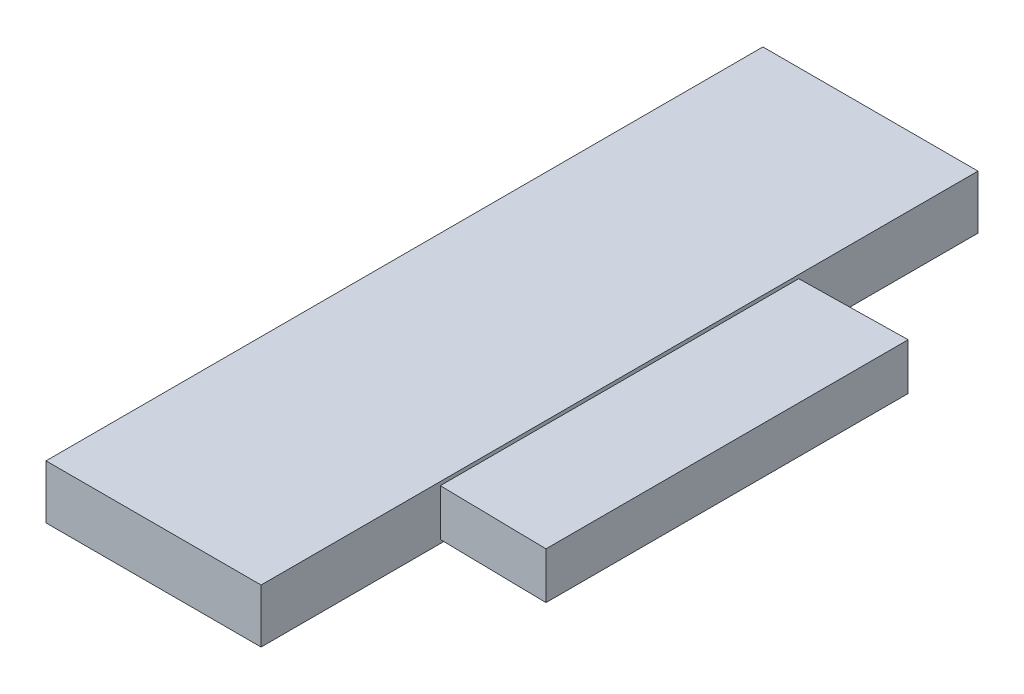
SolidWorks part; units mm, degrees
material "99.5% Aluminum Oxide (2)"
ref_plane "Front Plane" through (0, 0, 0) normal (0, 0, 1) x (1, 0, 0)
ref_plane "Top Plane" through (0, 0, 0) normal (0, 1, 0) x (1, 0, 0)
ref_plane "Right Plane" through (0, 0, 0) normal (1, 0, 0) x (0, 0, -1)
sketch "Sketch1" plane through (0, 0, 0) normal (0, 1, 0) x (1, 0, 0)
  line L1 (-30, 50) -> (0, 50)
  line L2 (-30, 50) -> (-30, -50)
  line L3 (-30, -50) -> (0, -50)
  line L7 (0, 50) -> (0, -50)
  dimension "D1" = 100
  dimension "D5" = 30
extrude "Boss-Extrude1" add sketch "Sketch1" along normal mid plane 7.5
sketch "Sketch2" plane through (0, 3.75, 0) normal (0, 1, 0) x (1, 0, 0)
  line L0 (0, 25) -> (15, 25.2618)
  line L1 (0, -50) -> (0, 50) construction
  line L2 (15, 25.2618) -> (15, -25.2618)
  line L3 (15, -25.2618) -> (0, -25)
  line L4 (0, -25) -> (0, 25)
  line L5 (0, 0) -> (15, 0) construction
  dimension "D1" = 50
  dimension "D2" = 91
  dimension "D3" = 15
extrude "Boss-Extrude2" add sketch "Sketch2" against normal blind 6.5 from offset 0.5
